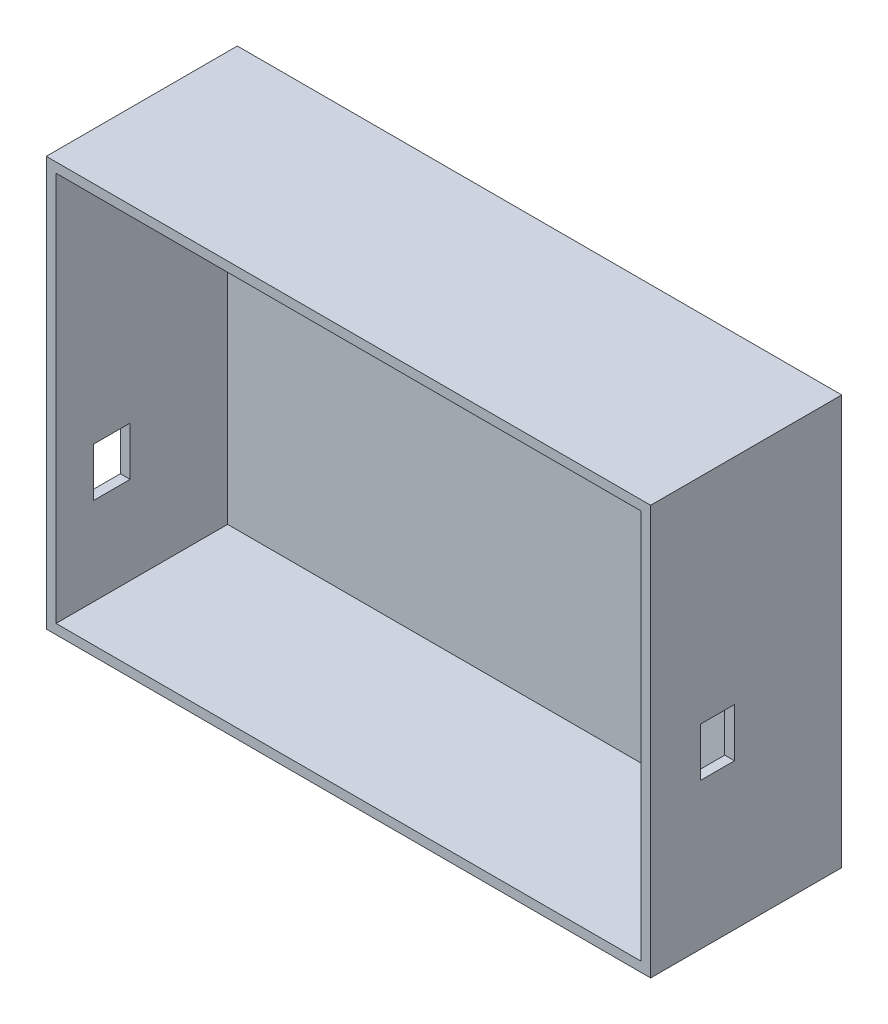
SolidWorks part; units mm, degrees
ref_plane "Front Plane" through (0, 0, 0) normal (0, 0, 1) x (1, 0, 0)
ref_plane "Top Plane" through (0, 0, 0) normal (0, 1, 0) x (1, 0, 0)
ref_plane "Right Plane" through (0, 0, 0) normal (1, 0, 0) x (0, 0, -1)
sketch "Sketch1" plane through (0, 0, 0) normal (0, 0, 1) x (1, 0, 0)
  line L1 (-78.74, -53.34) -> (78.74, -53.34)
  line L2 (-78.74, -53.34) -> (-78.74, 53.34)
  line L3 (-78.74, 53.34) -> (78.74, 53.34)
  line L4 (78.74, -53.34) -> (78.74, 53.34)
  line L5 (-78.74, -53.34) -> (78.74, 53.34) construction
  line L6 (-78.74, 53.34) -> (78.74, -53.34) construction
  point P0 (0, 0)
  dimension "D1" = 157.48
  dimension "D2" = 106.68
extrude "Boss-Extrude1" add sketch "Sketch1" along normal blind 49.784
sketch "Sketch3" plane through (0, 0, 49.784) normal (0, 0, 1) x (1, 0, 0)
  line L1 (-76.2, -50.8) -> (76.2, -50.8)
  line L2 (-76.2, -50.8) -> (-76.2, 50.8)
  line L3 (-76.2, 50.8) -> (76.2, 50.8)
  line L4 (76.2, -50.8) -> (76.2, 50.8)
  line L5 (-76.2, -50.8) -> (76.2, 50.8) construction
  line L6 (-76.2, 50.8) -> (76.2, -50.8) construction
  point P0 (0, 0)
  dimension "D1" = 152.4
  dimension "D2" = 101.6
extrude "Cut-Extrude1" cut sketch "Sketch3" against normal blind 44.704
sketch "Sketch4" plane through (78.74, 0, 0) normal (1, 0, 0) x (0, 0, -1)
  line L0 (-49.784, -53.34) -> (0, -53.34) construction
  line L1 (-36.83, -15.24) -> (-27.94, -15.24)
  line L2 (-36.83, -15.24) -> (-36.83, -2.54)
  line L3 (-36.83, -2.54) -> (-27.94, -2.54)
  line L4 (-27.94, -15.24) -> (-27.94, -2.54)
  line L5 (-36.83, -15.24) -> (-27.94, -2.54) construction
  line L6 (-36.83, -2.54) -> (-27.94, -15.24) construction
  line L7 (0, -53.34) -> (0, 53.34) construction
  point P0 (-32.385, -8.89)
  dimension "D1" = 12.7
  dimension "D2" = 8.89
  dimension "D3" = 38.1
  dimension "D4" = 27.94
extrude "Cut-Extrude2" cut sketch "Sketch4" against normal blind 43.18
sketch "Sketch6" plane through (-78.74, 0, 0) normal (-1, 0, 0) x (0, 0, 1)
  line L0 (0, 53.34) -> (0, -53.34) construction
  line L1 (30.48, -15.24) -> (40.005, -15.24)
  line L2 (30.48, -15.24) -> (30.48, -27.94)
  line L3 (30.48, -27.94) -> (40.005, -27.94)
  line L4 (40.005, -15.24) -> (40.005, -27.94)
  line L5 (30.48, -15.24) -> (40.005, -27.94) construction
  line L6 (30.48, -27.94) -> (40.005, -15.24) construction
  line L7 (49.784, -53.34) -> (0, -53.34) construction
  point P0 (35.2425, -21.59)
  dimension "D1" = 12.7
  dimension "D2" = 9.525
  dimension "D3" = 30.48
  dimension "D4" = 25.4
extrude "Cut-Extrude3" cut sketch "Sketch6" against normal blind 43.18
